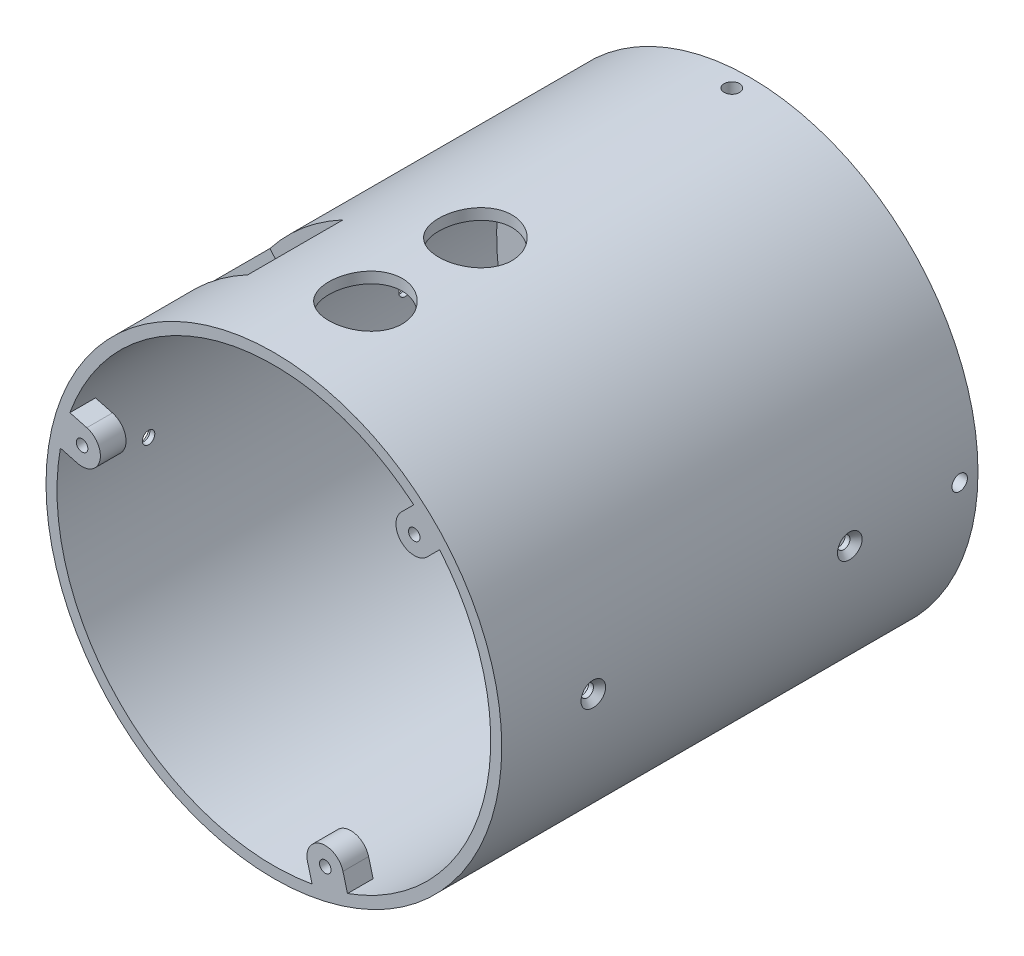
SolidWorks part; units mm, degrees
ref_plane "Ön Düzlem" through (0, 0, 0) normal (0, 0, 1) x (1, 0, 0)
ref_plane "Üst Düzlem" through (0, 0, 0) normal (0, 1, 0) x (1, 0, 0)
ref_plane "Sağ Düzlem" through (0, 0, 0) normal (1, 0, 0) x (0, 0, -1)
sketch "Çizim1" plane through (0, 0, 0) normal (0, 0, 1) x (1, 0, 0)
  circle A0 centre (0, 0) radius 62.2
  dimension "D1" = 124.4
extrude "Yükseklik-Ekstrüzyon1" add sketch "Çizim1" along normal blind 10
sketch "Çizim2" plane through (0, 0, 10) normal (0, 0, 1) x (1, 0, 0)
  circle A0 centre (0, 0) radius 62.2
  dimension "D1" = 124.4
extrude "Ekstrüzyon-İnce1" add sketch "Çizim2" along normal blind 120 thin thin type one direction reverse wall 3
ref_plane "Düzlem1" through (0, 62.2, 0) normal (0, 1, 0) x (1, 0, 0)
sketch "Çizim3" plane through (0, 62.2, 0) normal (0, 1, 0) x (1, 0, 0)
  line L0 (0, -130) -> (0, -75) construction
  line L1 (-62.2, -130) -> (62.2, -130) construction
  circle A0 centre (0, -75) radius 10
  circle A1 centre (0, -105) radius 10
  dimension "D2" = 20
  dimension "D1" = 55
  dimension "D3" = 30
extrude "Kes-Ekstrüzyon1" cut sketch "Çizim3" against normal blind 20
sketch "Çizim4" plane through (0, 0, 130) normal (0, 0, 1) x (1, 0, 0)
  line L0 (0, 0) -> (0, 35.442) construction
  line L1 (0, 0) -> (-39.9814, 47.648) construction
  line L3 (-76.5874, 16.9319) -> (-3.3754, 78.364) construction
  circle A1 centre (0, 0) radius 62.2 construction
  point P20 (-39.9814, 47.648)
  dimension "D1" = 40
sketch "Çizim6" plane through (0, 0, 0) normal (0, 0, -1) x (-1, 0, 0)
  line L0 (0, 0) -> (39.9814, 47.648) construction
ref_plane "Düzlem2" through (-39.9814, 47.648, 0) normal (0.6428, -0.766, 0) x (-0.766, -0.6428, 0)
sketch "Çizim7" plane through (-39.9814, 47.648, 0) normal (0.6428, -0.766, 0) x (-0.766, -0.6428, 0)
  line L0 (0, -130) -> (0, -95) construction
  line L2 (13, -82) -> (-13, -82)
  line L3 (13, -82) -> (13, -108)
  line L4 (13, -108) -> (-13, -108)
  line L5 (-13, -82) -> (-13, -108)
  line L6 (13, -82) -> (-13, -108) construction
  line L7 (13, -108) -> (-13, -82) construction
  dimension "D1" = 35
  dimension "D2" = 26
  dimension "D3" = 26
extrude "Kes-Ekstrüzyon2" cut sketch "Çizim7" along normal blind 20
sketch "Çizim8" plane through (0, 0, 130) normal (0, 0, 1) x (1, 0, 0)
  line L0 (0, 0) -> (41.8607, 41.8607) construction
  line L1 (0, 0) -> (0, 35.442) construction
  line L2 (38.3252, 45.3963) -> (45.3963, 38.3252)
  line L3 (38.3252, 45.3963) -> (34.7897, 41.8607)
  line L4 (45.3963, 38.3252) -> (41.8607, 34.7897)
  circle A0 centre (0, 0) radius 59.2 construction
  arc A1 (34.7897, 41.8607) -> (41.8607, 34.7897) centre (38.3252, 38.3252) ccw
  point P10 (41.8607, 41.8607)
  dimension "D1" = 45
  dimension "D2" = 10
  dimension "D3" = 5
  dimension "D4" = 5
  dimension "D5" = 5
extrude "Yükseklik-Ekstrüzyon2" add sketch "Çizim8" against normal blind 7
pattern_circular "Dairesel Kaplama1" count 3 over 360 about axis through (0, 0, 0) along (0, 0, 1) of "Yükseklik-Ekstrüzyon2"
hole_wizard "M3x0.5 Helisarmal İçin Dişli Delik1" positions "3B Çizim1" profile "Çizim12" tap size "M3x0.5" standard "Helicoil® Metric"
sketch3d "3B Çizim1"
  line L0 (-52.3532, 14.028, 123) -> (-52.3532, 14.028, 130) construction
  point P0 (-52.3532, 14.028, 130)
sketch "Çizim12" plane through (-52.3532, 14.028, 130) normal (1, 0, 0) x (0, -1, 0)
  line L0 (0, 0) -> (0, 8.4464)
  line L1 (0, 8.4464) -> (1.575, 7.5)
  line L2 (1.575, 7.5) -> (1.575, 0)
  line L5 (1.575, 0) -> (0, 0)
  line L10 (0, 8.4464) -> (-1.575, 7.5) construction
  line L11 (0, -6.35) -> (0, 107.95) construction
  dimension "Tap Drill Dia." = 3.15
  dimension "Tap Drill Depth" = 7.5
  dimension "Drill Angle" = 118
cosmetic thread "Delik Dişi1" parameters "D1"=3.5, "D2"=3.716
pattern_circular "Dairesel Kaplama2" count 4 over 360 skipping 1, 2, 3 of "M3x0.5 Helisarmal İçin Dişli Delik1"
cosmetic thread "Delik Dişi2" parameters "D1"=3.5, "D2"=3.716
cosmetic thread "Delik Dişi3" parameters "D1"=3.5, "D2"=3.716
ref_plane "Düzlem3" through (0, 62.2, 0) normal (0, 1, 0) x (1, 0, 0)
sketch "Çizim13" plane through (0, 62.2, 0) normal (0, 1, 0) x (1, 0, 0)
  line L0 (0, 0) -> (0, -5) construction
  point P1 (0, -5)
  point P7 (0, -5)
  dimension "D1" = 5
hole_wizard "M4x0.7 Helisarmal İçin Dişli Delik2" positions "Çizim13" profile "Çizim14" tap size "M4x0.7" standard "Helicoil® Metric"
sketch "Çizim14" plane through (0, 62.2, 5) normal (1, 0, 0) x (0, 0, 1)
  line L0 (0, 0) -> (0, 11.4618)
  line L1 (0, 11.4618) -> (2.1, 10.2)
  line L2 (2.1, 10.2) -> (2.1, 0)
  line L5 (2.1, 0) -> (0, 0)
  line L10 (0, 11.4618) -> (-2.1, 10.2) construction
  line L11 (0, -6.35) -> (0, 107.95) construction
  dimension "Tap Drill Dia." = 4.2
  dimension "Tap Drill Depth" = 10.2
  dimension "Drill Angle" = 118
cosmetic thread "Delik Dişi4" parameters "D1"=4.7, "D2"=5.007
pattern_circular "Dairesel Kaplama3" count 4 over 360 about axis through (0, 0, 0) along (0, 0, 1) of "M4x0.7 Helisarmal İçin Dişli Delik2"
cosmetic thread "Delik Dişi5" parameters "D1"=4.7, "D2"=5.007
cosmetic thread "Delik Dişi6" parameters "D1"=4.7, "D2"=5.007
cosmetic thread "Delik Dişi7" parameters "D1"=4.7, "D2"=5.007
ref_plane "Düzlem4" through (62.2, 0, 0) normal (1, 0, 0) x (0, 0, -1)
sketch "Çizim15" plane through (62.2, 0, 0) normal (1, 0, 0) x (0, 0, -1)
  line L0 (0, 0) -> (-35, 0) construction
  line L1 (0, -62.2) -> (0, 62.2) construction
  line L2 (-130, 0) -> (-105, 0) construction
  line L3 (-130, 62.2) -> (-130, -62.2) construction
  point P1 (-35, 0)
  point P5 (-105, 0)
  point P13 (-105, 0)
  point P17 (-35, 0)
  dimension "D1" = 35
  dimension "D2" = 25
hole_wizard "M3 Altıgen Alyan Havşa Başlı Kör Vida İçin Havşa1" positions "Çizim15" profile "Çizim16" countersink size "M3" standard "ISO"
sketch "Çizim16" plane through (62.2, 0, 35) normal (0, 1, 0) x (0, 0, -1)
  line L0 (0, 0) -> (0, 11.2215)
  line L1 (0, 11.2215) -> (1.7, 10.2)
  line L2 (1.7, 10.2) -> (1.7, 1.66)
  line L3 (1.7, 1.66) -> (3.36, 0)
  line L5 (3.36, 0) -> (0, 0)
  line L6 (-1.7, 1.66) -> (-3.36, 0) construction
  line L10 (0, 11.2215) -> (-1.7, 10.2) construction
  line L11 (0, -6.35) -> (0, 107.95) construction
  dimension "Hole Dia." = 3.4
  dimension "Hole Depth" = 10.2
  dimension "Near C'Sink Dia." = 6.72
  dimension "Near C'Sink Angle" = 90
  dimension "Drill Angle" = 118
pattern_circular "Dairesel Kaplama4" count 2 over 360 of "M3 Altıgen Alyan Havşa Başlı Kör Vida İçin Havşa1"
pattern_circular "Dairesel Kaplama5" count 3 over 360 about axis through (0, 0, 0) along (0, 0, 1) of "M3x0.5 Helisarmal İçin Dişli Delik1"
cosmetic thread "Delik Dişi8" parameters "D1"=3.5, "D2"=3.716
cosmetic thread "Delik Dişi9" parameters "D1"=3.5, "D2"=3.716
